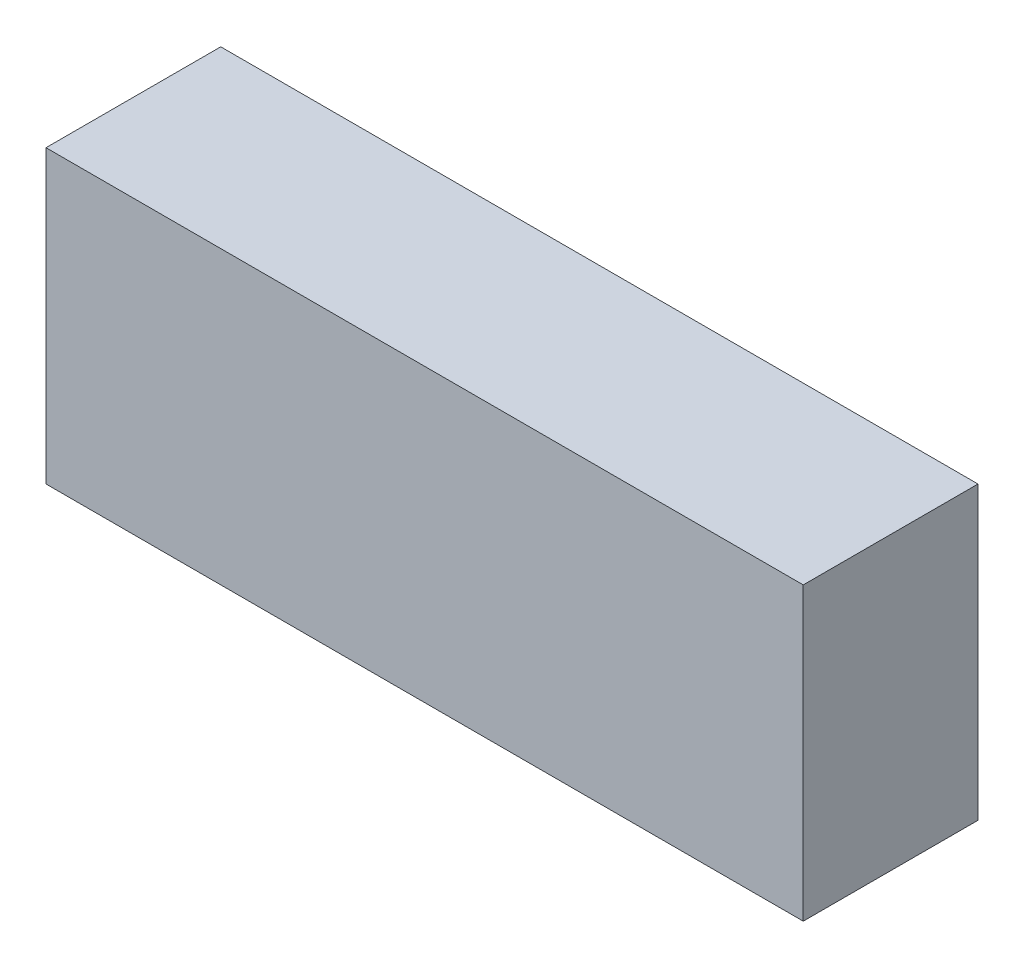
SolidWorks part; units mm, degrees
ref_plane "Front Plane" through (0, 0, 0) normal (0, 0, 1) x (1, 0, 0)
ref_plane "Top Plane" through (0, 0, 0) normal (0, 1, 0) x (1, 0, 0)
ref_plane "Right Plane" through (0, 0, 0) normal (1, 0, 0) x (0, 0, -1)
sketch "Sketch1" plane through (0, 0, 0) normal (0, 0, 1) x (1, 0, 0)
  line L1 (0, 0) -> (13, 0)
  line L2 (0, 0) -> (0, 5)
  line L3 (0, 5) -> (13, 5)
  line L4 (13, 0) -> (13, 5)
  dimension "D1" = 5
  dimension "D2" = 13
extrude "Boss-Extrude1" add sketch "Sketch1" along normal blind 3
